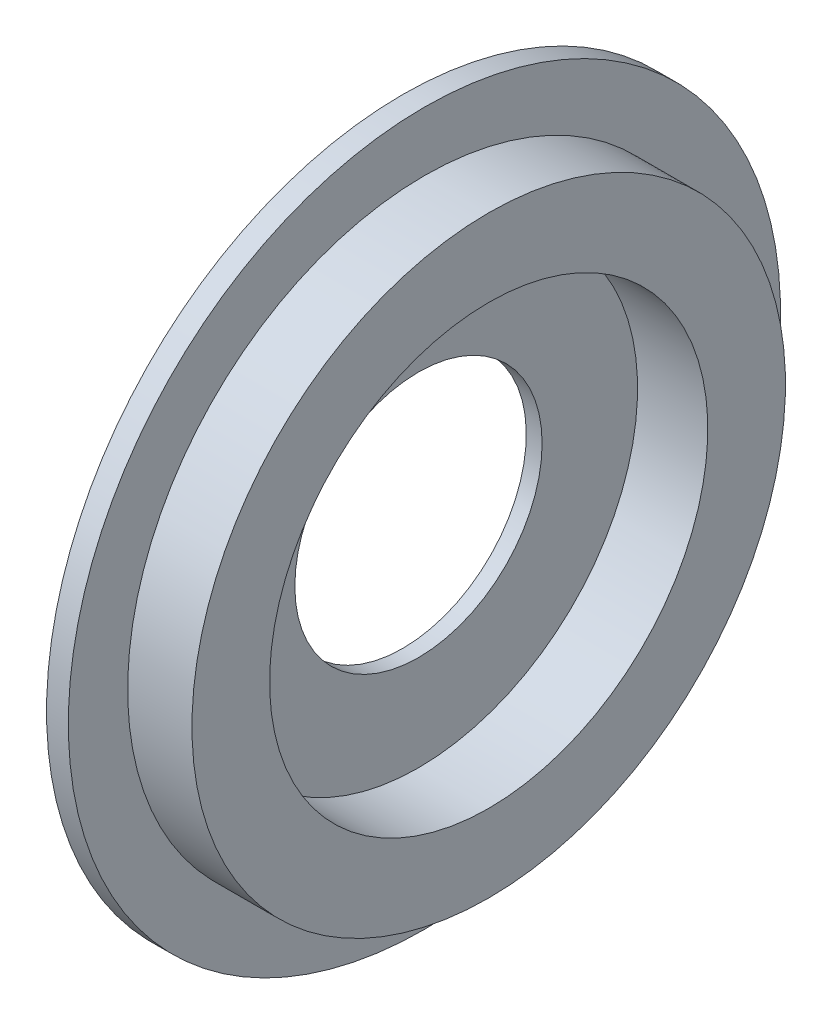
SolidWorks part; units mm, degrees
ref_plane "Ebene vorne" through (0, 0, 0) normal (0, 0, 1) x (1, 0, 0)
ref_plane "Ebene oben" through (0, 0, 0) normal (0, 1, 0) x (1, 0, 0)
ref_plane "Ebene rechts" through (0, 0, 0) normal (1, 0, 0) x (0, 0, -1)
sketch "Skizze1" plane through (0, 0, 0) normal (0, 0, 1) x (1, 0, 0)
  line L0 (0, 0) -> (0, 18)
  line L1 (0, 18) -> (1.1, 18)
  line L2 (1.1, 18) -> (1.1, 15)
  line L3 (1.1, 15) -> (4.35, 15)
  line L4 (4.35, 15) -> (4.35, 11.075)
  line L5 (4.35, 11.075) -> (0.8, 11.075)
  line L6 (0.8, 11.075) -> (0.8, 0)
  line L7 (0.8, 0) -> (0, 0)
  dimension "D1" = 18
  dimension "D2" = 11.075
  dimension "D3" = 3.25
  dimension "D5" = 3
  dimension "D6" = 0.8
  dimension "D7" = 3.55
revolve "Rotation2" add sketch "Skizze1" angle 360 about L7
sketch "Skizze2" plane through (0, 0, 0) normal (-1, 0, 0) x (0, 0, 1)
  circle A0 centre (0, 0) radius 6.25
  dimension "D1" = 12.5
extrude "Schnitt-Linear austragen1" cut sketch "Skizze2" against normal through all
